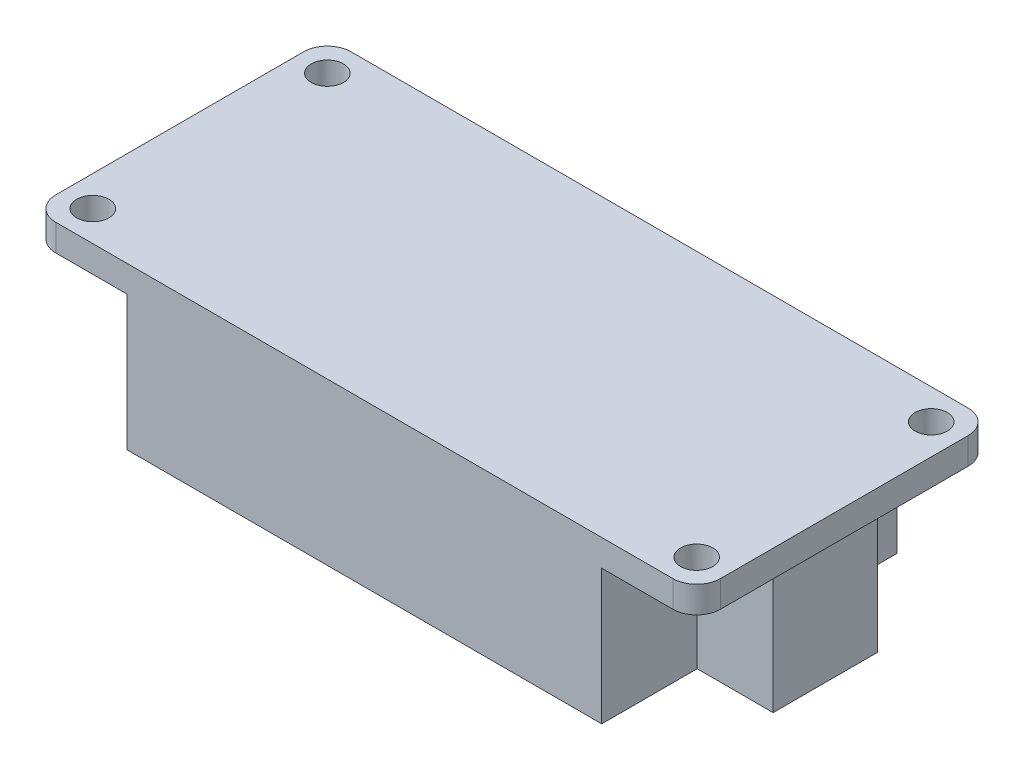
SolidWorks part; units mm, degrees
ref_plane "Front Plane" through (0, 0, 0) normal (0, 0, 1) x (1, 0, 0)
ref_plane "Top Plane" through (0, 0, 0) normal (0, 1, 0) x (1, 0, 0)
ref_plane "Right Plane" through (0, 0, 0) normal (1, 0, 0) x (0, 0, -1)
sketch "Sketch1" plane through (0, 0, 0) normal (0, 1, 0) x (1, 0, 0)
  line L0 (0, 21.05) -> (0, 31.1)
  line L1 (0, 0) -> (50, 0)
  line L2 (0, 0) -> (0, 10.05)
  line L3 (0, 31.1) -> (50, 31.1)
  line L4 (50, 0) -> (50, 10.05)
  line L5 (0, 21.05) -> (-8, 21.05)
  line L6 (50, 21.05) -> (50, 31.1)
  line L7 (0, 10.05) -> (-8, 10.05)
  line L8 (-8, 21.05) -> (-8, 10.05)
  line L9 (50, 21.05) -> (58, 21.05)
  line L10 (25, 31.1) -> (25, 0) construction
  line L11 (50, 10.05) -> (58, 10.05)
  line L12 (58, 21.05) -> (58, 10.05)
  line L13 (25, 15.55) -> (13.1818, 15.55) construction
  dimension "D1" = 50
  dimension "D2" = 66
  dimension "D3" = 31.1
  dimension "D4" = 11
extrude "Boss-Extrude1" add sketch "Sketch1" along normal blind 14.2
sketch "Sketch2" plane through (0, 14.2, 0) normal (0, 1, 0) x (1, 0, 0)
  line L0 (25, 31.1) -> (25, 0) construction
  line L1 (57.5, 31.1) -> (-7.5, 31.1)
  line L2 (60, 28.6) -> (60, 2.5)
  line L3 (57.5, 0) -> (-7.5, 0)
  line L4 (-10, 28.6) -> (-10, 2.5)
  line L5 (60, 31.1) -> (-10, 0) construction
  line L6 (60, 0) -> (-10, 31.1) construction
  line L7 (50, 31.1) -> (0, 31.1) construction
  line L8 (0, 0) -> (50, 0) construction
  arc A0 (57.5, 31.1) -> (60, 28.6) centre (57.5, 28.6) cw
  arc A1 (60, 2.5) -> (57.5, 0) centre (57.5, 2.5) cw
  arc A2 (-7.5, 0) -> (-10, 2.5) centre (-7.5, 2.5) cw
  arc A3 (-7.5, 31.1) -> (-10, 28.6) centre (-7.5, 28.6) ccw
  point P0 (25, 15.55)
  dimension "D2" = 2.5
  dimension "D1" = 70
extrude "Boss-Extrude2" add sketch "Sketch2" along normal blind 2.8
sketch "Sketch3" plane through (0, 17, 0) normal (0, 1, 0) x (1, 0, 0)
  line L0 (25, 31.1) -> (25, 0) construction
  line L1 (57.5, 31.1) -> (-7.5, 31.1) construction
  line L2 (-7.5, 0) -> (57.5, 0) construction
  line L3 (-10, 15.55) -> (25, 15.55) construction
  line L4 (-10, 28.6) -> (-10, 2.5) construction
  circle A0 centre (-6.8, 3.2) radius 1.7
  circle A1 centre (56.8, 3.2) radius 1.7
  circle A2 centre (56.8, 27.9) radius 1.7
  circle A3 centre (-6.8, 27.9) radius 1.7
  dimension "D1" = 3.2
  dimension "D3" = 3.4
  dimension "D2" = 3.2
extrude "Cut-Extrude2" cut sketch "Sketch3" against normal through all
